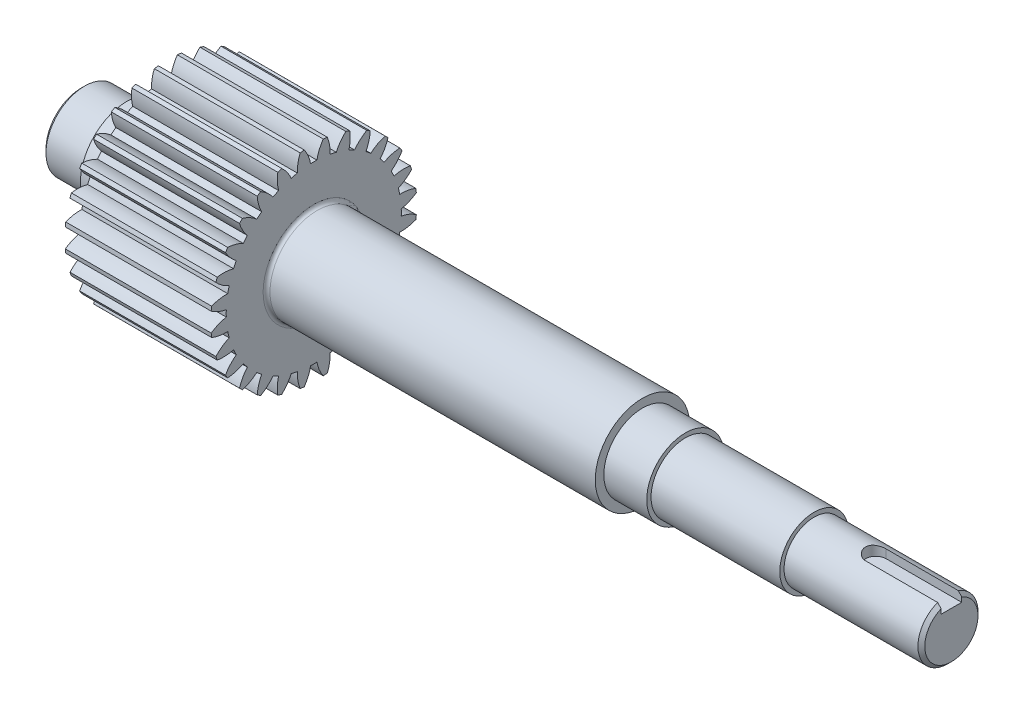
SolidWorks part; units mm, degrees
material "AISI 4340 Steel, annealed"
ref_plane "Plane1" through (0, 0, 0) normal (0, 0, 1) x (1, 0, 0)
ref_plane "Plane2" through (0, 0, 0) normal (0, 1, 0) x (1, 0, 0)
ref_plane "Plane3" through (0, 0, 0) normal (1, 0, 0) x (0, 0, -1)
other "Configuration Table"
sketch "HoldingSke" plane through (0, 0, 0) normal (0, 1, 0) x (1, 0, 0)
  line L0 (0, 0) -> (0.2207, -0.1174)
  line L1 (-15, 0) -> (100, 0) construction
  line L2 (0, 0) -> (-2.1039, 2.3779)
  line L3 (0, 0) -> (-11.863, 4.5341)
  line L4 (0, 0) -> (7.6251, 4.0544)
  line L5 (0, 0) -> (-46.8476, -17.4728)
  line L6 (0, 0) -> (-70.4618, -47.5408)
  line L7 (-2.1039, 2.3779) -> (16.1923, 85.3855)
  line L8 (-76.2, 54.61) -> (-76.1, 54.61)
  line L9 (-71.009, 38.7566) -> (-53.1078, 45.2721)
  line L10 (-76.2, 71.12) -> (104.1128, 71.12)
  line L11 (0, 0) -> (-85, 0)
  line L12 (-76.2, 101.6) -> (-76.073, 101.6)
  line L13 (24.9733, 27.94) -> (52.9518, 28.4284)
  line L14 (24.9733, 27.94) -> (24.9743, 27.94)
  line L15 (24.9733, 27.94) -> (100.4006, 29.5858)
  line L16 (-63.627, -4) -> (-12.827, -4)
  circle A0 centre (0, 0) radius 0.4
  circle A1 centre (0, 0) radius 37.5
  circle A2 centre (0, 0) radius 37.5
  circle A3 centre (0, 0) radius 0.4
  dimension "MHD" = 75
  dimension "Hub_dia" = 75
  dimension "Bore" = 0.8
  dimension "MBD" = 0.8
  dimension "Num_teeth" = 28
  dimension "Pitch" = 0.25
  dimension "Overall_len" = 50
  dimension "Show_teeth" = 28
  dimension "Thickness" = 85
  dimension "OAL" = 85.0001
  dimension "T_dim" = 0.1
  dimension "Ap" = 20
  dimension "H" = 19.05
  dimension "Pitch_radius" = 180.3128
  dimension "Width" = 85
  dimension "Backlash" = 0.127
  dimension "Addendum_fac" = 1
  dimension "Dedendum_fac" = 1.25
  dimension "Clearance_fac" = 0.25
  dimension "Dedendum_add" = 0.001
  dimension "Module" = 4
sketch "BasProSke" plane through (0, 0, 0) normal (0, 1, 0) x (1, 0, 0)
  line L0 (-10, 0) -> (60, 0) construction
  line L1 (0, 0) -> (0, 60)
  line L2 (0, 0) -> (85, 0)
  line L3 (85, 0) -> (85, 60)
  line L4 (85, 60) -> (0, 60)
  dimension "Thickness" = 85
  dimension "Diameter" = 120
revolve "Base-Revolve" add sketch "BasProSke" angle 360 about L0
sketch "TooCutSke" plane through (0, 0, 0) normal (1, 0, 0) x (0, 0, -1)
  line L1 (0, 0) -> (0, 107) construction
  line L2 (0, 0) -> (-3.3621, 55.899) construction
  line L3 (0, 0) -> (-12.523, 111.1446) construction
  line L4 (-3.3621, 55.899) -> (-6.2615, 55.5723) construction
  arc A0 (1.846, 50.9656) -> (-1.846, 50.9656) centre (0, 0) ccw
  arc A1 (5.5418, 59.769) -> (-5.5418, 59.769) centre (0, 0) ccw
  circle A2 centre (0, 0) radius 56 construction
  circle A3 centre (0, 0) radius 52.6228 construction
  arc A4 (-1.846, 50.9656) -> (-5.5418, 59.769) centre (-23.8732, 46.8959) ccw
  arc A5 (5.5418, 59.769) -> (1.846, 50.9656) centre (23.8732, 46.8959) ccw
  dimension "Root_dia" = 101.998
  dimension "Overcut_dia" = 120.0508
  dimension "Pitch_dia" = 112
  dimension "Base_dia" = 105.2456
  dimension "Flank_rad" = 22.4
  dimension "Half_ang" = 6.429
  dimension "Half_CT" = 2.9177
extrude "ToothCut" cut sketch "TooCutSke" along normal through all
fillet "Breaks" [suppressed] radius 0.08
fillet "RootFillets" [suppressed] radius 1.001
pattern_circular "TeethCuts" count 28 every 12.857 about axis through (-10, 0, 0) along (1, 0, 0) of "ToothCut", "RootFillets", "Breaks"
sketch "HubNeaOneSke" plane through (0, 0, 0) normal (-1, 0, 0) x (0, 0, 1)
  circle A0 centre (0, 0) radius 37.5
  dimension "Diameter" = 75
extrude "HubNearOne" [suppressed] add sketch "HubNeaOneSke" along normal blind 38.0001
sketch "HubNeaBotSke" plane through (0, 0, 0) normal (-1, 0, 0) x (0, 0, 1)
  circle A0 centre (0, 0) radius 37.5
  dimension "Diameter" = 75
extrude "HubNearBoth" [suppressed] add sketch "HubNeaBotSke" along normal blind 19
ref_plane "FarPln" through (85, 0, 0) normal (1, 0, 0) x (0, 0, -1)
sketch "HubFarSke" plane through (85, 0, 0) normal (1, 0, 0) x (0, 0, -1)
  circle A0 centre (0, 0) radius 37.5
  dimension "Diameter" = 75
extrude "HubFar" [suppressed] add sketch "HubFarSke" along normal blind 19
sketch "BorSke" plane through (0, 0, 0) normal (1, 0, 0) x (0, 0, -1)
  circle A0 centre (0, 0) radius 0.4
  dimension "Diameter" = 0.8
extrude "Bore" cut sketch "BorSke" along normal mid plane 170.0001
sketch "KeySke" plane through (0, 0, 0) normal (1, 0, 0) x (0, 0, -1)
  line L0 (-0.05, 0) -> (-0.05, 0.5)
  line L1 (-0.05, 0.5) -> (0.05, 0.5)
  line L2 (0.05, 0.5) -> (0.05, 0)
  line L3 (0, 0) -> (0, 34) construction
  line L4 (-0.05, 0) -> (0.05, 0)
  dimension "Offset" = 0.5
  dimension "Width" = 0.1
extrude "Keyway" [suppressed] cut sketch "KeySke" along normal mid plane 170.0001
pattern_circular "Keyway2" [suppressed] count 2 every 90 about axis through (-10, 0, 0) along (1, 0, 0)
sketch "Sketch1" plane through (0, 0, 0) normal (0, 0, 1) x (1, 0, 0)
  line L0 (0, 0) -> (456.5, 0)
  line L1 (0, 1.846) -> (0, -1.846) construction
  line L2 (456.5, 0) -> (456.5, 17.5)
  line L3 (456.5, 17.5) -> (376.5, 17.5)
  line L4 (376.5, 17.5) -> (376.5, 20)
  line L5 (376.5, 20) -> (301.5, 20)
  line L6 (301.5, 20) -> (301.5, 22.5)
  line L7 (301.5, 22.5) -> (276.5, 22.5)
  line L8 (276.5, 22.5) -> (276.5, 27.5)
  line L9 (276.5, 27.5) -> (-23.5, 27.5)
  line L10 (-23.5, 27.5) -> (-23.5, 22.5)
  line L11 (-23.5, 22.5) -> (-50.5, 22.5)
  line L12 (-50.5, 22.5) -> (-50.5, 0)
  line L13 (-50.5, 0) -> (0, 0)
  line L14 (309.8766, 0) -> (-140.423, 0) construction
  line L15 (0, 41.57) -> (0, 33.2198) construction
  dimension "D1" = 45
  dimension "D2" = 55
  dimension "D3" = 35
  dimension "D4" = 40
  dimension "D5" = 45
  dimension "D6" = 80
  dimension "D7" = 75
  dimension "D8" = 25
  dimension "D9" = 191.5
  dimension "D10" = 23.5
  dimension "D11" = 50.5
revolve "Revolve1" add sketch "Sketch1" angle 360 about L14
fillet "Fillet1" radius 2 2 edges at (0, 0, -27.5) (85, 0, 27.5)
chamfer "Chamfer1" distance 2 angle 45 2 edges at (-50.5, 22.5, 0) (456.5, 17.5, 0)
sketch "Sketch2" plane through (0, 0, 0) normal (0, 1, 0) x (1, 0, 0)
  line L0 (412.5, 0) -> (500.5, 0) construction
  line L1 (412.5, 6) -> (500.5, 6)
  line L2 (412.5, -6) -> (500.5, -6)
  line L3 (456.5, -15.5) -> (456.5, 15.5) construction
  arc A0 (412.5, 6) -> (412.5, -6) centre (412.5, 0) ccw
  arc A1 (500.5, -6) -> (500.5, 6) centre (500.5, 0) ccw
  point P3 (456.5, 0)
  dimension "D1" = 6
  dimension "D2" = 88
extrude "Cut-Extrude1" cut sketch "Sketch2" along normal through all from offset 11.5
equation "' \"Module@HoldingSke\" = 6.35"
equation "' \"Num_teeth@HoldingSke\" = 12"
equation "' \"Ap@HoldingSke\" =  20"
equation "' \"Ap@HoldingSke\" = 20"
equation "' \"Width@HoldingSke\" = 0.5 * 25.4"
equation "' \"Hub_dia@HoldingSke\"= 1 * 25.4"
equation "' \"Hub_dia@HoldingSke\" = 1 * 25.4"
equation "' \"Overall_len@HoldingSke\" = 1.0 * 25.4"
equation "' \"Bore@HoldingSke\" = 0.75 * 25.4"
equation "' \"T_dim@HoldingSke\" = 0.1 * 25.4"
equation "' \"Width@KeySke\" = 0.25 * 25.4"
equation "' \"Show_teeth@HoldingSke\" = 13"
equation "' \"Backlash@HoldingSke\" = 0.009 * 25.4"
equation "' \"Addendum_fac@HoldingSke\" = 1.0"
equation "' \"Dedendum_fac@HoldingSke\" = 1.25"
equation "' \"Dedendum_add@HoldingSke\" = 0.00005 * 25.4"
equation "' \"Clearance_fac@HoldingSke\" = 0.25"
equation "\"Pitch@HoldingSke\" = 1 / \"Module@HoldingSke\""
equation "\"Overcut_dia@TooCutSke\" = (\"Num_teeth@HoldingSke\" + 2 * \"Addendum_fac@HoldingSke\") / \"Pitch@HoldingSke\" + 0.002 * 25.4"
equation "\"Pitch_dia@TooCutSke\" = \"Num_teeth@HoldingSke\" / \"Pitch@HoldingSke\""
equation "\"Base_dia@TooCutSke\" = \"Num_teeth@HoldingSke\" / \"Pitch@HoldingSke\" * cos((\"Ap@HoldingSke\"  * 3.14159265 / 180))"
equation "\"Root_dia@TooCutSke\" = (\"Num_teeth@HoldingSke\" + 2) / \"Pitch@HoldingSke\" - 2 * (\"Addendum_fac@HoldingSke\" + \"Dedendum_fac@HoldingSke\") / \"Pitch@HoldingSke\" - \"Dedendum_add@HoldingSke\" * 2"
equation "\"Half_ang@TooCutSke\" = 180 / \"Num_teeth@HoldingSke\""
equation "\"Half_CT@TooCutSke\" = \"Num_teeth@HoldingSke\" / \"Pitch@HoldingSke\" * sin((3.14159265 / 2 / \"Num_teeth@HoldingSke\")) / 2 - 7 * \"Backlash@HoldingSke\" / 4"
equation "\"Flank_rad@TooCutSke\" = \"Num_teeth@HoldingSke\" / \"Pitch@HoldingSke\" / 5"
equation "\"Radius@RootFillets\" = \"Clearance_fac@HoldingSke\" / \"Pitch@HoldingSke\" + \"Dedendum_add@HoldingSke\""
equation "\"Break_rad@Breaks\" = 0.02 / \"Pitch@HoldingSke\""
equation "\"Thickness@HoldingSke\" = \"Width@HoldingSke\""
equation "\"OAL@HoldingSke\" = \"Thickness@HoldingSke\""
equation "\"MHD@HoldingSke\" = (\"Num_teeth@HoldingSke\" + 2) / \"Pitch@HoldingSke\" - 2 * (\"Addendum_fac@HoldingSke\" + \"Dedendum_fac@HoldingSke\")  / \"Pitch@HoldingSke\" - \"Dedendum_add@HoldingSke\" * 2"
equation "\"MBD@HoldingSke\" = (\"Num_teeth@HoldingSke\" + 2) / \"Pitch@HoldingSke\" - 2 * (\"Addendum_fac@HoldingSke\" + \"Dedendum_fac@HoldingSke\")  / \"Pitch@HoldingSke\" - \"Dedendum_add@HoldingSke\" * 2 - 0.002 * 25.4"
equation "\"MHD@HoldingSke\" = ((sgn( \"MHD@HoldingSke\" - \"Hub_dia@HoldingSke\" )-1)*( \"MHD@HoldingSke\" - \"Hub_dia@HoldingSke\" ))/-2+ \"Hub_dia@HoldingSke\""
equation "\"MBD@HoldingSke\" = ((sgn( \"MBD@HoldingSke\" - \"Bore@HoldingSke\" )-1)*( \"MBD@HoldingSke\" - \"Bore@HoldingSke\" ))/-2+ \"Bore@HoldingSke\""
equation "\"OAL@HoldingSke\" = ((sgn( \"OAL@HoldingSke\" - \"Overall_len@HoldingSke\" )+1)*( \"OAL@HoldingSke\" - \"Overall_len@HoldingSke\" ))/2 + \"Overall_len@HoldingSke\" + 0.000002 * 25.4"
equation "\"Num_teeth@TeethCuts\" = int( \"Show_teeth@HoldingSke\" ) + 1"
equation "\"Num_teeth@TeethCuts\" = ((sgn( \"Num_teeth@TeethCuts\" - \"Num_teeth@HoldingSke\" )-1)*( \"Num_teeth@TeethCuts\" - \"Num_teeth@HoldingSke\" ))/-2+ \"Num_teeth@HoldingSke\""
equation "\"Num_teeth@TeethCuts\" = ((sgn( \"Num_teeth@TeethCuts\" - 2.0)+1)*( \"Num_teeth@TeethCuts\" - 2.0))/2 +2.0"
equation "\"Angle@TeethCuts\" = 360.0 / \"Num_teeth@HoldingSke\""
equation "\"Diameter@BasProSke\" = (\"Num_teeth@HoldingSke\" + 2 * \"Addendum_fac@HoldingSke\") / \"Pitch@HoldingSke\""
equation "\"Thickness@BasProSke\"  = \"Thickness@HoldingSke\""
equation "' \"Fillet_rad@BasProSke\" =  \"Thickness@HoldingSke\" * 0.05"
equation "' \"Fillet_rad@BasProSke\" = \"Thickness@HoldingSke\" * 0.05"
equation "\"MHD@HoldingSke\" = ((sgn( \"MHD@HoldingSke\" - \"Root_dia@TooCutSke\" )-1)*( \"MHD@HoldingSke\" - \"Root_dia@TooCutSke\" ))/-2+ \"Root_dia@TooCutSke\""
equation "\"Diameter@HubNeaOneSke\" = \"MHD@HoldingSke\""
equation "\"Length@HubNearOne\" = \"OAL@HoldingSke\" - \"Thickness@BasProSke\""
equation "\"Diameter@HubNeaBotSke\" = \"MHD@HoldingSke\""
equation "\"Length@HubNearBoth\" = ( \"OAL@HoldingSke\" - \"Thickness@BasProSke\" ) / 2.0"
equation "\"Thickness@FarPln\" = \"Thickness@BasProSke\""
equation "\"Diameter@HubFarSke\" = \"MHD@HoldingSke\""
equation "\"Length@HubFar\" = ( \"OAL@HoldingSke\" - \"Thickness@BasProSke\" ) / 2.0"
equation "\"Diameter@BorSke\" = \"MBD@HoldingSke\""
equation "\"D1@Bore\" = \"OAL@HoldingSke\" * 2.0"
equation "\"D1@Keyway\" = \"OAL@HoldingSke\" * 2.0"
equation "\"Offset@KeySke\" = \"T_dim@HoldingSke\" + \"MBD@HoldingSke\" / 2.0"
equation "\"D2@Sketch2\"=100-12"
